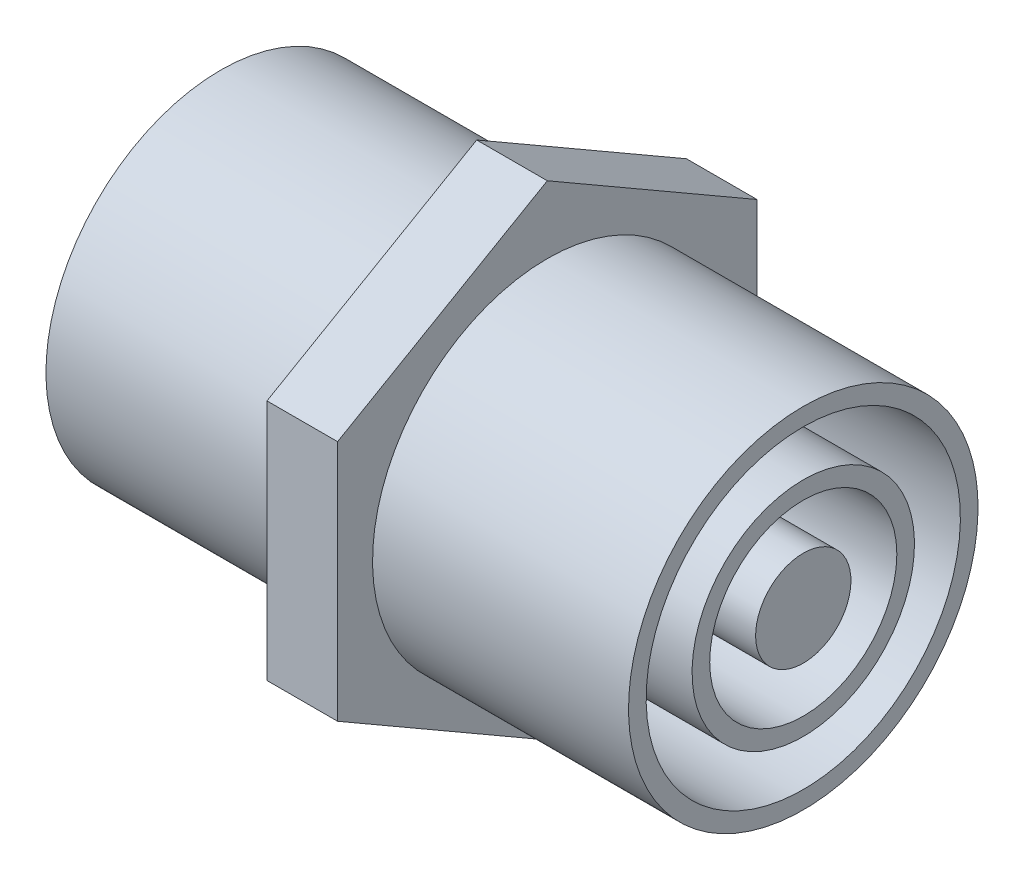
SolidWorks part; units mm, degrees
ref_plane "Front Plane" through (0, 0, 0) normal (0, 0, 1) x (1, 0, 0)
ref_plane "Top Plane" through (0, 0, 0) normal (0, 1, 0) x (1, 0, 0)
ref_plane "Right Plane" through (0, 0, 0) normal (1, 0, 0) x (0, 0, -1)
sketch "Sketch1" plane through (0, 0, 0) normal (0, 0, 1) x (1, 0, 0)
  line L0 (0, 0) -> (0, 1.35)
  line L1 (0, 1.35) -> (7.25, 1.35)
  line L2 (7.25, 1.35) -> (7.25, 2.65)
  line L3 (7.25, 2.65) -> (0, 2.65)
  line L4 (0, 2.65) -> (0, 3.15)
  line L5 (0, 3.15) -> (7.25, 3.15)
  line L7 (7.25, 5.85) -> (8.25, 5.85)
  line L8 (8.25, 5.85) -> (8.25, 0)
  line L9 (8.25, 0) -> (0, 0)
  line L10 (7.25, 5.85) -> (7.25, 4.95)
  line L11 (7.25, 4.95) -> (0, 4.95)
  line L12 (0, 4.95) -> (0, 4.45)
  line L13 (0, 4.45) -> (7.25, 4.45)
  line L14 (7.25, 4.45) -> (7.25, 3.15)
  dimension "D1" = 7.25
  dimension "D2" = 5.85
  dimension "D3" = 0.5
  dimension "D4" = 1.3
  dimension "D5" = 1
  dimension "D6" = 0.9
revolve "Revolve1" add sketch "Sketch1" angle 360 about L9
sketch "Sketch2" plane through (8.25, 0, 0) normal (1, 0, 0) x (0, 0, -1)
  line L0 (0, 0) -> (0, 6.8589) construction
  line L1 (5.94, -3.4295) -> (5.94, 3.4295)
  line L2 (5.94, 3.4295) -> (0, 6.8589)
  line L3 (0, 6.8589) -> (-5.94, 3.4295)
  line L4 (-5.94, 3.4295) -> (-5.94, -3.4295)
  line L5 (-5.94, -3.4295) -> (0, -6.8589)
  line L6 (0, -6.8589) -> (5.94, -3.4295)
  circle A0 centre (0, 0) radius 5.94 construction
  dimension "D1" = 11.88
extrude "Boss-Extrude1" add sketch "Sketch2" against normal blind 1 contours L3 L4 L5 L6 L1 L2
mirror "Mirror1" of bodies 102
